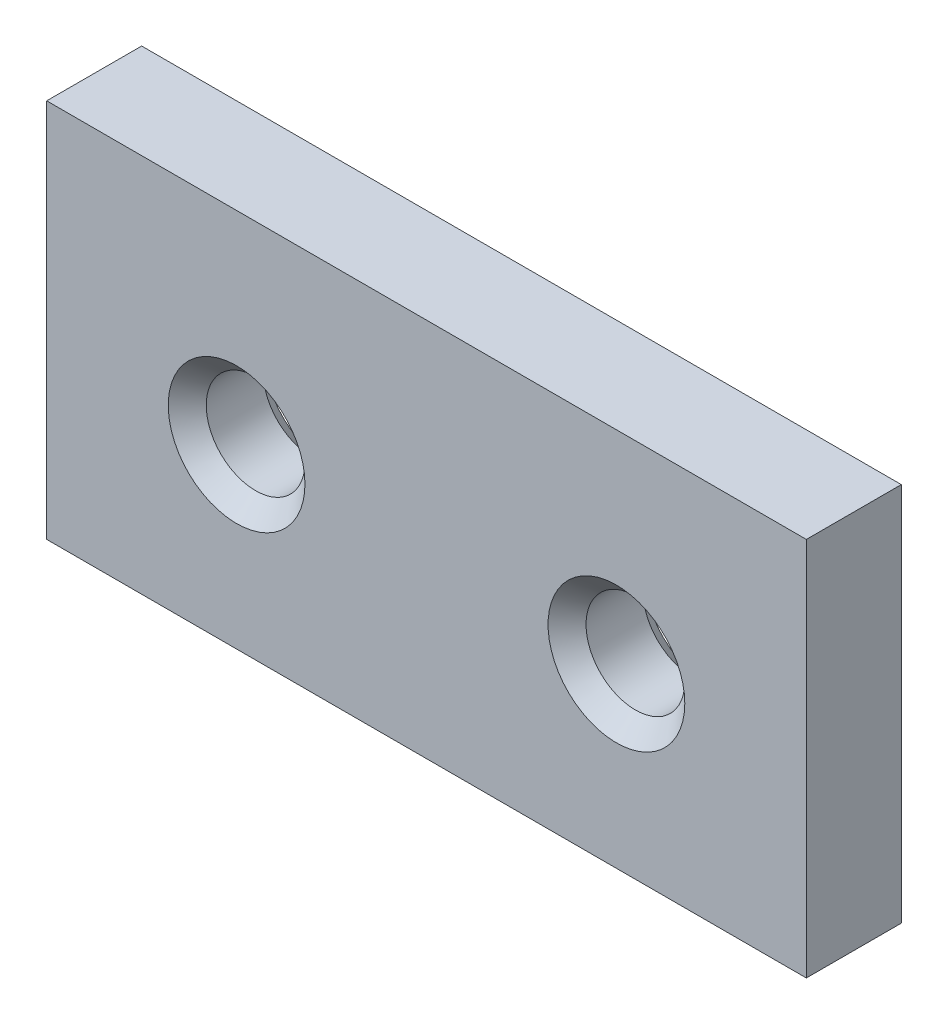
SolidWorks part; units mm, degrees
ref_plane "Front" through (0, 0, 0) normal (0, 0, 1) x (1, 0, 0)
ref_plane "Top" through (0, 0, 0) normal (0, 1, 0) x (1, 0, 0)
ref_plane "Right" through (0, 0, 0) normal (1, 0, 0) x (0, 0, -1)
sketch "Çizim1" plane through (0, 0, 0) normal (0, 0, 1) x (1, 0, 0)
  line L1 (-71.2983, 16.0465) -> (-31.2983, 16.0465)
  line L2 (-71.2983, 16.0465) -> (-71.2983, -3.9535)
  line L3 (-71.2983, -3.9535) -> (-31.2983, -3.9535)
  line L4 (-31.2983, 16.0465) -> (-31.2983, -3.9535)
  dimension "D1" = 40
  dimension "D2" = 20
extrude "Yükseklik-Ekstrüzyon1" add sketch "Çizim1" along normal blind 5
sketch "Çizim2" plane through (0, 0, 5) normal (0, 0, 1) x (1, 0, 0)
  line L0 (-71.2983, 16.0465) -> (-71.2983, -3.9535) construction
  line L1 (-31.2983, -3.9535) -> (-31.2983, 16.0465) construction
  circle A0 centre (-61.2983, 5.3671) radius 2.6
  circle A1 centre (-41.2983, 5.3671) radius 2.6
  point P4 (0, 0)
  dimension "D1" = 5.2
  dimension "D2" = 5.2
  dimension "D3" = 10
  dimension "D4" = 10
extrude "Kes-Ekstrüzyon1" cut sketch "Çizim2" against normal blind 5
chamfer "Pah1" distance 1 angle 45 4 edges at (-38.6983, 5.3671, 5) (-58.6983, 5.3671, 5) (-58.6983, 5.3671, 0) (-38.6983, 5.3671, 0)
